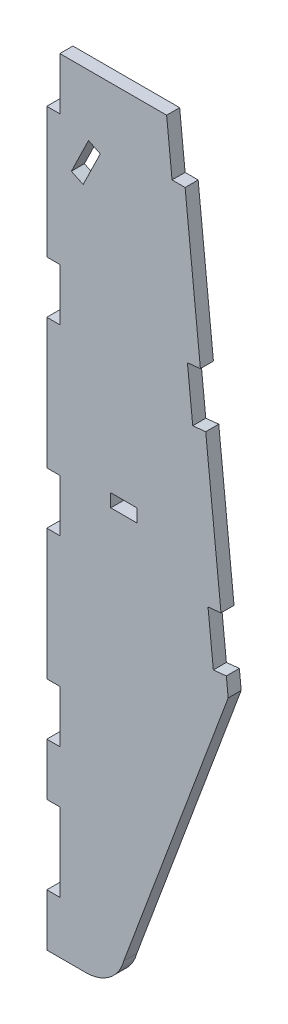
SolidWorks part; units mm, degrees
material "Papier ondulé"
ref_plane "Plan de face" through (0, 0, 0) normal (0, 0, 1) x (1, 0, 0)
ref_plane "Plan de dessus" through (0, 0, 0) normal (0, 1, 0) x (1, 0, 0)
ref_plane "Plan de droite" through (0, 0, 0) normal (1, 0, 0) x (0, 0, -1)
sketch "Esquisse1" plane through (0, 0, 0) normal (0, 0, 1) x (1, 0, 0)
  line L0 (0, 0) -> (43, 0)
  line L1 (43, 0) -> (43, -20.4431)
  line L2 (43, -20.4431) -> (48, -20.4431)
  line L3 (48, -20.4431) -> (53.8565, -77.644)
  line L4 (53.8565, -77.644) -> (48.8825, -78.1533)
  line L5 (48.8825, -78.1533) -> (50.9195, -98.0493)
  line L6 (50.9195, -98.0493) -> (55.8935, -97.54)
  line L7 (-5, -20) -> (-5, -70)
  line L8 (55.8935, -97.54) -> (61.75, -154.741)
  line L9 (61.75, -154.741) -> (56.776, -155.2503)
  line L10 (56.776, -155.2503) -> (58.813, -175.1463)
  line L11 (-5, -70) -> (0, -70)
  line L12 (0, -70) -> (0, -90)
  line L13 (0, 0) -> (0, -20)
  line L14 (0, -20) -> (-5, -20)
  line L15 (0, -90) -> (-5, -90)
  line L17 (10, -300) -> (10, -285) construction
  line L18 (10, -285) -> (24.4889, -288.8823) construction
  line L19 (0, -140) -> (19.5, -140) construction
  line L23 (-5, -90) -> (-5, -140)
  line L24 (-5, -140) -> (0, -140)
  line L25 (0, -140) -> (0, -160)
  line L26 (0, -160) -> (-5, -160)
  line L27 (-5, -160) -> (-5, -210)
  line L28 (-5, -210) -> (0, -210)
  line L29 (0, -210) -> (0, -230)
  line L30 (0, -230) -> (-5, -230)
  line L31 (-5, -230) -> (-5, -250)
  line L32 (-5, -250) -> (0, -250)
  line L33 (0, -250) -> (0, -280)
  line L34 (0, -280) -> (-5, -280)
  line L35 (-5, -280) -> (-5, -300)
  line L36 (-5, -300) -> (10, -300)
  line L37 (58.813, -175.1463) -> (63.787, -174.637)
  line L38 (63.787, -174.637) -> (64.5, -181.6006)
  line L39 (64.5, -181.6006) -> (24.4889, -288.8823)
  line L40 (19.5, -140) -> (19.5, -141) construction
  line L41 (-5, -56.1583) -> (11.0005, -23.3523) construction
  line L42 (19.5, -141) -> (29.5, -141)
  line L43 (19.5, -141) -> (19.5, -136)
  line L44 (19.5, -136) -> (29.5, -136)
  line L45 (29.5, -141) -> (29.5, -136)
  line L46 (11.0005, -23.3523) -> (4.425, -36.8342)
  line L47 (11.0005, -23.3523) -> (15.4945, -25.5442)
  line L48 (4.425, -36.8342) -> (8.9189, -39.0261)
  line L49 (15.4945, -25.5442) -> (8.9189, -39.0261)
  line L50 (64.5, -181.6006) -> (-5, -181.6006) construction
  line L51 (-5, -181.6006) -> (64.5, -181.6006) construction
  arc A0 (10, -300) -> (24.4889, -288.8823) centre (10, -285) ccw
extrude "Boss.-Extru.1" add sketch "Esquisse1" along normal blind 5
sketch "Esquisse2" plane through (0, 0, 5) normal (0, 0, 1) x (1, 0, 0)
  line L0 (64.5, -181.6006) -> (-5, -181.6006)
  line L1 (-5, -160) -> (-5, -210) construction
sketch "Esquisse3" plane through (0, 0, 0) normal (0, 0, -1) x (-1, 0, 0)
  line L0 (-48.8825, -78.1533) -> (-43, -20.4431) construction
  line L1 (-43, -20.4431) -> (-40.9162, 0)
  line L2 (-43, 0) -> (0, 0) construction
  line L3 (-40.9162, 0) -> (-43, 0)
  line L4 (-43, 0) -> (-43, -20.4431)
extrude "Enlèv. mat.-Extru.1" cut sketch "Esquisse3" against normal through all
